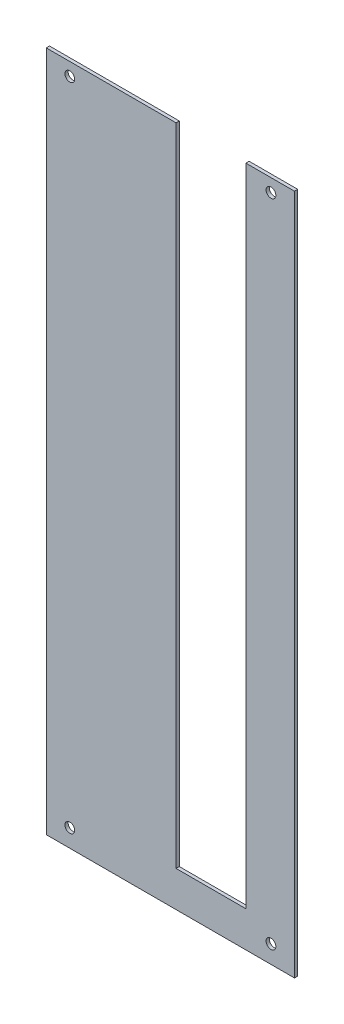
SolidWorks part; units mm, degrees
ref_plane "Front Plane" through (0, 0, 0) normal (0, 0, 1) x (1, 0, 0)
ref_plane "Top Plane" through (0, 0, 0) normal (0, 1, 0) x (1, 0, 0)
ref_plane "Right Plane" through (0, 0, 0) normal (1, 0, 0) x (0, 0, -1)
sketch "Sketch1" plane through (0, 0, 0) normal (0, 0, 1) x (1, 0, 0)
  line L1 (-76.5, -210) -> (76.5, -210)
  line L2 (-76.5, -210) -> (-76.5, 210)
  line L3 (-76.5, 210) -> (76.5, 210)
  line L4 (76.5, -210) -> (76.5, 210)
  line L5 (-76.5, -210) -> (76.5, 210) construction
  line L6 (-76.5, 210) -> (76.5, -210) construction
  point P0 (0, 0)
  dimension "D1" = 420
  dimension "D2" = 153
extrude "Boss-Extrude1" add sketch "Sketch1" along normal blind 2
sketch "Sketch2" plane through (0, 0, 0) normal (0, 0, -1) x (-1, 0, 0)
  line L0 (-46.5, 210) -> (-46.5, -188)
  line L1 (-76.5, 210) -> (76.5, 210) construction
  line L2 (-46.5, -188) -> (-3.5, -188)
  line L3 (-3.5, -188) -> (-3.5, 210)
  line L4 (-76.5, -210) -> (-76.5, 210) construction
  line L5 (76.5, 210) -> (76.5, -210) construction
  line L6 (76.5, -210) -> (-76.5, -210) construction
  line L7 (-46.5, 210) -> (-3.5, 210)
  dimension "D1" = 30
  dimension "D2" = 80
  dimension "D3" = 22
extrude "Cut-Extrude1" cut sketch "Sketch2" against normal up to next
sketch "Sketch3" plane through (0, 0, 0) normal (0, 0, -1) x (-1, 0, 0)
  line L0 (0, 0) -> (76.5, 0) construction
  line L1 (76.5, 210) -> (76.5, -210) construction
  line L2 (0, 0) -> (0, -210) construction
  line L3 (76.5, -210) -> (-76.5, -210) construction
  line L5 (-76.5, -210) -> (-76.5, 210) construction
  line L6 (-76.5, 210) -> (-46.5, 210) construction
  circle A4 centre (-62, 202) radius 3
  circle A5 centre (-62, -199) radius 3
  circle A6 centre (62, 202) radius 3
  circle A7 centre (62, -199) radius 3
  dimension "D1" = 8
  dimension "D2" = 6
  dimension "D4" = 14.5
  dimension "D3" = 11
  dimension "D5" = 14.5
extrude "Cut-Extrude2" cut sketch "Sketch3" against normal up to next
